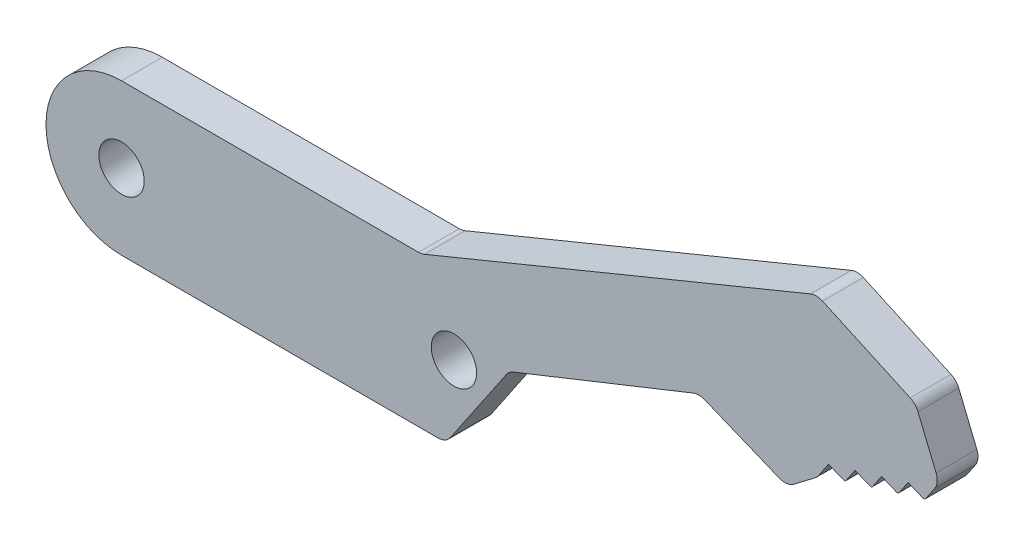
SolidWorks part; units mm, degrees
ref_plane "Front Plane" through (0, 0, 0) normal (0, 0, 1) x (1, 0, 0)
ref_plane "Top Plane" through (0, 0, 0) normal (0, 1, 0) x (1, 0, 0)
ref_plane "Right Plane" through (0, 0, 0) normal (1, 0, 0) x (0, 0, -1)
sketch "Sketch1" plane through (0, 0, 0) normal (0, 0, 1) x (1, 0, 0)
  line L0 (0, 5) -> (19.85, 5)
  line L1 (19.85, 5) -> (45.9962, 15.75)
  line L2 (45.9962, 15.75) -> (52.5575, 12.7612)
  line L3 (52.5575, 12.7612) -> (53.9075, 9.4779)
  line L4 (0, -5) -> (21.47, -5)
  line L5 (21.47, -5) -> (25.6444, 1.1586)
  line L6 (25.6444, 1.1586) -> (38.212, 6.17)
  line L7 (38.212, 6.17) -> (43.5199, 3.9974)
  line L8 (44.5077, 4.1297) -> (45.913, 5.2086)
  line L9 (46.1318, 5.4407) -> (46.7939, 6.4175)
  line L10 (46.7939, 6.4175) -> (47.8859, 5.9705)
  line L11 (47.8859, 5.9705) -> (48.548, 6.9472)
  line L12 (48.548, 6.9472) -> (49.64, 6.5003)
  line L13 (49.64, 6.5003) -> (50.3021, 7.477)
  line L14 (50.3021, 7.477) -> (51.3942, 7.03)
  line L15 (51.3942, 7.03) -> (52.0562, 8.0068)
  line L16 (52.0562, 8.0068) -> (53.1483, 7.5598)
  line L17 (53.1483, 7.5598) -> (53.8104, 8.5366)
  arc A0 (0, 5) -> (0, -5) centre (0, 0) ccw
  circle A1 centre (0, 0) radius 1.5
  circle A2 centre (22, 0) radius 1.5
  arc A3 (53.9075, 9.4779) -> (53.8104, 8.5366) centre (52.9826, 9.0976) cw
  arc A4 (45.913, 5.2086) -> (46.1318, 5.4407) centre (45.304, 6.0018) ccw
  arc A5 (43.5199, 3.9974) -> (44.5077, 4.1297) centre (43.8987, 4.9229) ccw
  point P30 (54.1117, 8.9811)
  point P35 (44.0518, 3.7797)
  dimension "D1" = 10
  dimension "D2" = 3
  dimension "D3" = 3
  dimension "D6" = 22
  dimension "D22" = 1
  dimension "D23" = 1
  dimension "D24" = 1
  dimension "D4" = 157.65
  dimension "D5" = 10.75
  dimension "D7" = 124.13
  dimension "D8" = 133.16
  dimension "D9" = 1.18
  dimension "D10" = 7.21
  dimension "D11" = 3.55
  dimension "D12" = 7.44
  dimension "D13" = 21.47
  dimension "D14" = 19.85
  dimension "D15" = 214.13
  dimension "D16" = 224
  dimension "D17" = 13.53
  dimension "D18" = 6.31
  dimension "D19" = 1.18
  dimension "D20" = 1.18
  dimension "D21" = 136.84
extrude "Boss-Extrude1" add sketch "Sketch1" against normal blind 2.7
fillet "Fillet1" radius 0.15 4 edges at (47.8859, 5.9705, -1.35) (49.64, 6.5003, -1.35) (53.1483, 7.5598, -1.35) (51.3942, 7.03, -1.35)
fillet "Fillet2" radius 1 3 edges at (21.47, -5, -1.35) (52.5575, 12.7612, -1.35) (45.9962, 15.75, -1.35)
fillet "Fillet3" radius 1 2 edges at (25.6444, 1.1586, -1.35) (38.212, 6.17, -1.35)
fillet "Fillet4" radius 1 1 edges at (19.85, 5, -1.35)
